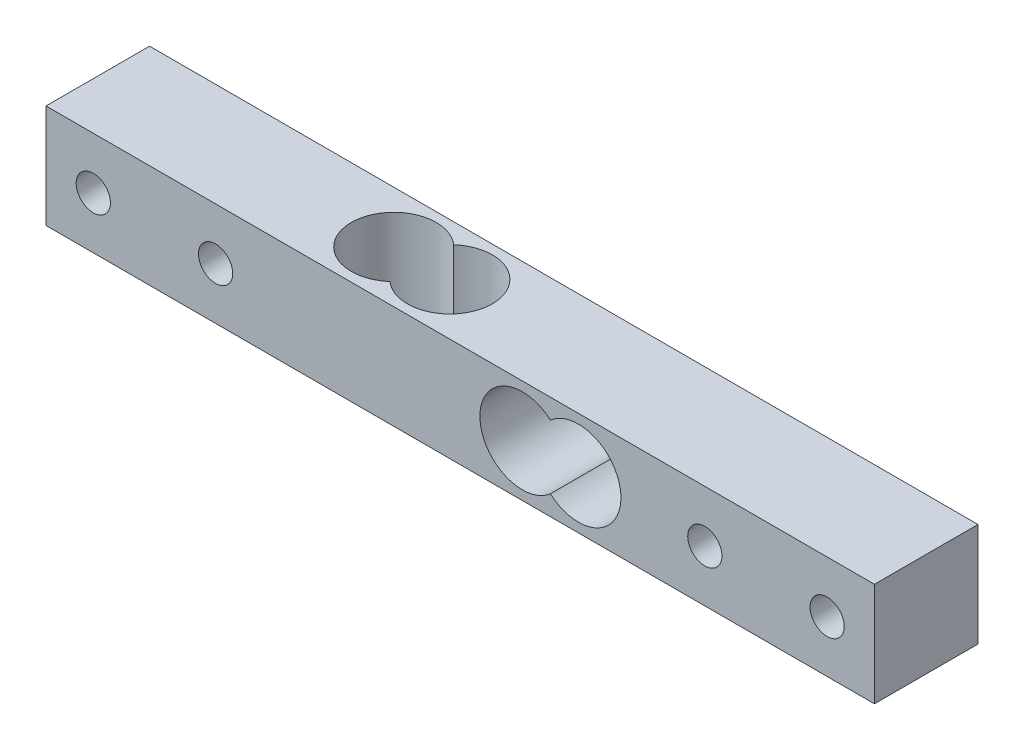
SolidWorks part; units mm, degrees
ref_plane "Front Plane" through (0, 0, 0) normal (0, 0, 1) x (1, 0, 0)
ref_plane "Top Plane" through (0, 0, 0) normal (0, 1, 0) x (1, 0, 0)
ref_plane "Right Plane" through (0, 0, 0) normal (1, 0, 0) x (0, 0, -1)
sketch "Sketch1" plane through (0, 0, 0) normal (1, 0, 0) x (0, 0, -1)
  line L1 (6.35, 6.35) -> (-6.35, 6.35)
  line L2 (6.35, 6.35) -> (6.35, -6.35)
  line L3 (6.35, -6.35) -> (-6.35, -6.35)
  line L4 (-6.35, 6.35) -> (-6.35, -6.35)
  line L5 (0, -6.35) -> (0, 6.35) construction
  line L6 (6.35, 0) -> (-6.35, 0) construction
  point P0 (0, 0)
  dimension "D1" = 12.7
  dimension "D2" = 12.7
extrude "Boss-Extrude1" add sketch "Sketch1" along normal mid plane 101.6
sketch "Sketch2" plane through (0, 6.35, 0) normal (0, 1, 0) x (1, 0, 0)
  circle A0 centre (-14.5, 0) radius 5.21
  circle A1 centre (-7.62, 0) radius 5.21
  dimension "D1" = 10.42
  dimension "D2" = 17.3
  dimension "D3" = 7.62
sketch "Sketch3" plane through (0, 0, -6.35) normal (0, 0, -1) x (-1, 0, 0)
  circle A0 centre (-14.5, 0) radius 5.21
  circle A1 centre (-7.62, 0) radius 5.21
  dimension "D1" = 10.42
  dimension "D3" = 7.62
  dimension "D2" = 17.3
extrude "Cut-Extrude1" cut sketch "Sketch2" against normal blind 101.6 contours A1 A0 | A0 A1 | A0 A1
extrude "Cut-Extrude2" cut sketch "Sketch3" against normal blind 101.6 contours A0 A1 | A0 A1 | A1 A0
hole_wizard "M5x0.8 Tapped Hole2" positions "Sketch9" profile "Sketch8" tap size "M5x0.8" standard "ANSI Metric"
sketch "Sketch9" plane through (0, 0, -6.35) normal (0, 0, -1) x (-1, 0, 0)
  point P0 (-45, 0)
  point P2 (-30, 0)
  point P7 (30, 0)
  point P9 (45, 0)
  dimension "D1" = 15
  dimension "D2" = 30
  dimension "D3" = 30
  dimension "D4" = 15
sketch "Sketch8" plane through (45, 0, -6.35) normal (1, 0, 0) x (0, 1, 0)
  line L0 (0, 0) -> (0, 15.2618)
  line L1 (0, 15.2618) -> (2.1, 14)
  line L2 (2.1, 14) -> (2.1, 0)
  line L5 (2.1, 0) -> (0, 0)
  line L10 (0, 15.2618) -> (-2.1, 14) construction
  line L11 (0, -6.35) -> (0, 107.95) construction
  dimension "Tap Drill Dia." = 4.2
  dimension "Tap Drill Depth" = 14
  dimension "Drill Angle" = 118
cosmetic thread "Hole Thread3" parameters "D1"=10, "D2"=5
cosmetic thread "Hole Thread4" parameters "D1"=10, "D2"=5
cosmetic thread "Hole Thread5" parameters "D1"=10, "D2"=5
cosmetic thread "Hole Thread6" parameters "D1"=10, "D2"=5
